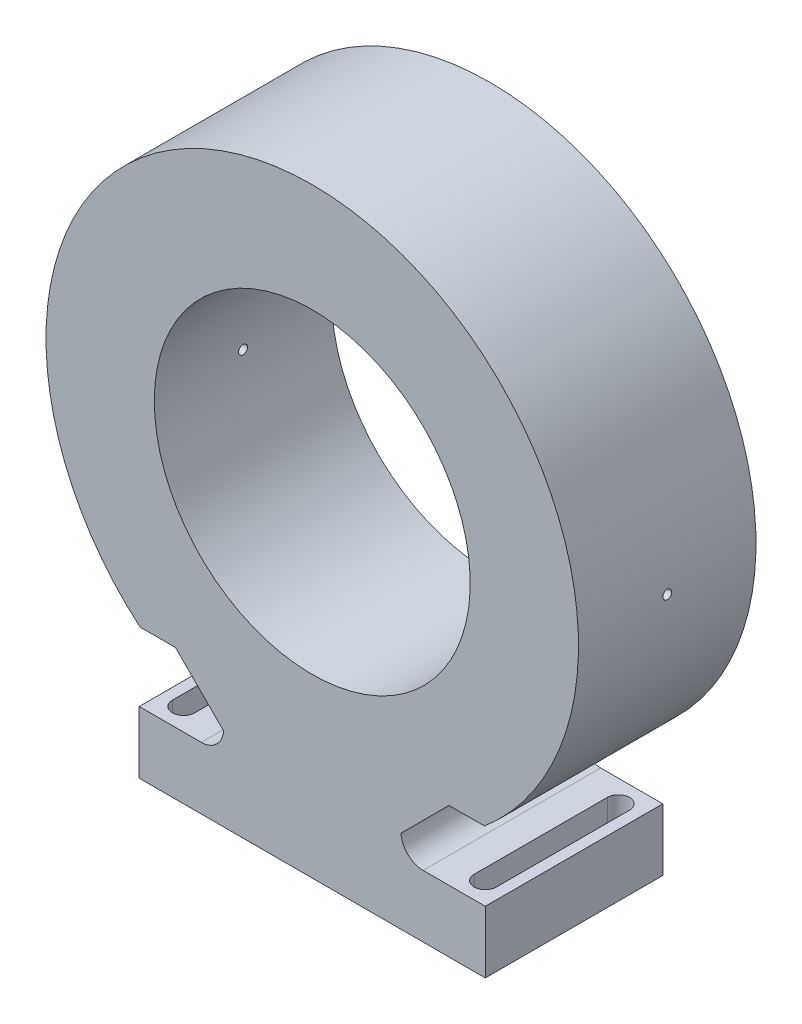
SolidWorks part; units mm, degrees
ref_plane "Front Plane" through (0, 0, 0) normal (0, 0, 1) x (1, 0, 0)
ref_plane "Top Plane" through (0, 0, 0) normal (0, 1, 0) x (1, 0, 0)
ref_plane "Right Plane" through (0, 0, 0) normal (1, 0, 0) x (0, 0, -1)
sketch "Sketch2" plane through (0, 0, 0) normal (0, 0, 1) x (1, 0, 0)
  line L7 (31.7432, -77.898) -> (49.5232, -77.898)
  line L8 (49.5232, -77.898) -> (49.5232, -95.678)
  line L9 (49.5232, -95.678) -> (-49.5232, -95.678)
  line L10 (-49.5232, -95.678) -> (-49.5232, -77.898)
  line L11 (-49.5232, -77.898) -> (-31.7432, -77.898)
  arc A0 (-59.3246, 47.8229) -> (-25.4, -71.842) centre (0, 0) ccw
  arc A1 (-35.1993, 28.3749) -> (35.1993, 28.3749) centre (0, 0) ccw
  arc A2 (31.7432, -77.898) -> (25.4, -71.842) centre (31.7432, -71.548) cw
  arc A4 (-31.7432, -77.898) -> (-25.4, -71.842) centre (-31.7432, -71.548) ccw
  arc A5 (25.4, -71.842) -> (59.3246, 47.8229) centre (0, 0) ccw
  arc A6 (-59.3246, 47.8229) -> (59.3246, 47.8229) centre (0, 0) cw
  arc A7 (-35.1993, 28.3749) -> (35.1993, 28.3749) centre (0, 0) cw
  point P9 (0, -78.703)
  point P10 (-10.2654, -57.6636)
  point P12 (10.2654, -57.6636)
  point P17 (0, -95.678)
  dimension "D1" = 45.212
  dimension "D7" = 0
  dimension "D8" = 6.35
  dimension "D9" = 6.35
  dimension "D10" = 76.2
  dimension "D12" = 0
  dimension "D2" = 17.78
  dimension "D3" = 17.78
  dimension "D4" = 17.78
  dimension "D5" = 17.78
  dimension "D6" = 50.8
  dimension "D11" = 25.4
extrude "Boss-Extrude1" add sketch "Sketch2" along normal blind 50.8
sketch "Sketch3" plane through (0, -95.678, 0) normal (0, -1, 0) x (1, 0, 0)
  line L0 (-43.1732, 44.45) -> (-43.1732, 6.35) construction
  line L1 (-39.9982, 44.45) -> (-39.9982, 6.35)
  line L2 (-46.3482, 44.45) -> (-46.3482, 6.35)
  line L3 (43.1732, 44.45) -> (43.1732, 6.35) construction
  line L4 (46.3482, 44.45) -> (46.3482, 6.35)
  line L5 (39.9982, 44.45) -> (39.9982, 6.35)
  line L6 (-49.5232, 50.8) -> (-49.5232, 0) construction
  line L7 (49.5232, 50.8) -> (49.5232, 0) construction
  line L8 (-49.5232, 50.8) -> (49.5232, 50.8) construction
  line L9 (-49.5232, 0) -> (49.5232, 0) construction
  arc A0 (-39.9982, 44.45) -> (-46.3482, 44.45) centre (-43.1732, 44.45) ccw
  arc A1 (-46.3482, 6.35) -> (-39.9982, 6.35) centre (-43.1732, 6.35) ccw
  arc A2 (46.3482, 44.45) -> (39.9982, 44.45) centre (43.1732, 44.45) ccw
  arc A3 (39.9982, 6.35) -> (46.3482, 6.35) centre (43.1732, 6.35) ccw
  point P2 (-43.1732, 25.4)
  point P9 (43.1732, 25.4)
  dimension "D3" = 6.35
  dimension "D1" = 6.35
  dimension "D2" = 6.35
  dimension "D4" = 6.35
  dimension "D5" = 6.35
  dimension "D6" = 6.35
  dimension "D7" = 6.35
  dimension "D8" = 6.35
extrude "Cut-Extrude1" cut sketch "Sketch3" against normal blind 25.4
sketch "Sketch4" plane through (0, 0, 50.8) normal (0, 0, 1) x (1, 0, 0)
  line L0 (25.4, -71.842) -> (39.1342, -58.1078)
  line L1 (39.1342, -58.1078) -> (49.2942, -58.1078)
  line L2 (-25.4, -71.842) -> (-39.1342, -58.1078)
  line L3 (-39.1342, -58.1078) -> (-49.2942, -58.1078)
  arc A0 (25.4, -71.842) -> (-25.4, -71.842) centre (0, 0) ccw construction
  arc A1 (25.4, -71.842) -> (-25.4, -71.842) centre (0, 0) ccw construction
  arc A2 (-49.2942, -58.1078) -> (-25.4, -71.842) centre (-30.48, -53.0278) ccw
  arc A3 (49.2942, -58.1078) -> (25.4, -71.842) centre (30.48, -53.0278) cw
  dimension "D1" = 135
  dimension "D2" = 10.16
  dimension "D3" = 10.16
  dimension "D4" = 135
extrude "Cut-Extrude2" cut sketch "Sketch4" against normal blind 72.136
sketch "Sketch5" plane through (0, 0, 0) normal (1, 0, 0) x (0, 0, -1)
  line L0 (0, -58.1078) -> (0, 76.2) construction
  circle A0 centre (-25.4, 0) radius 1.27
  dimension "D1" = 2.54
  dimension "D2" = 25.4
extrude "Cut-Extrude3" cut sketch "Sketch5" against normal blind 90.424 and the other way blind 113.284
